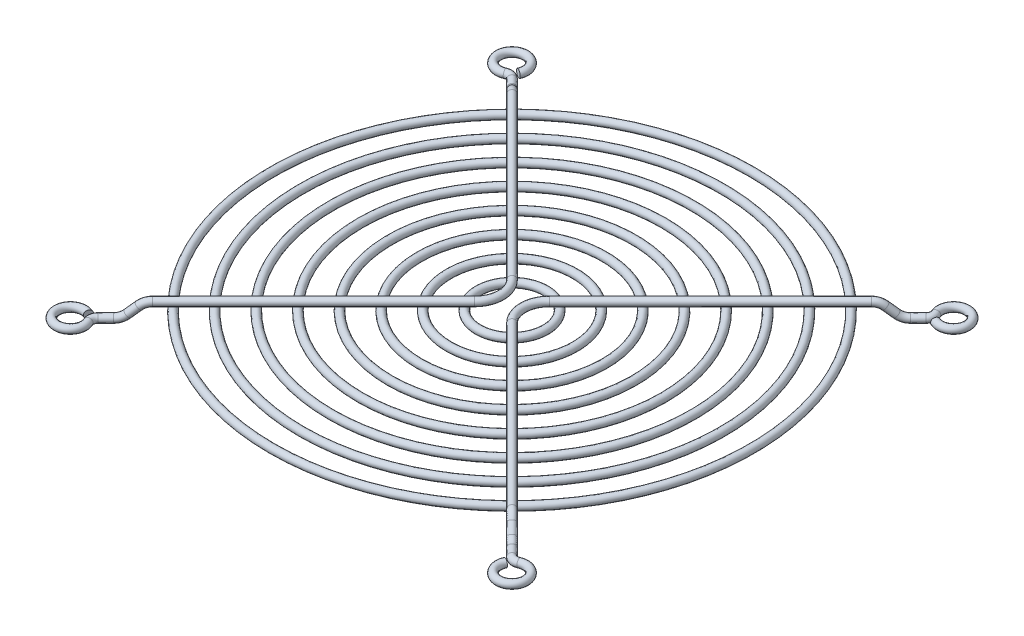
SolidWorks part; units mm, degrees
material "AISI 304"
ref_plane "Front" through (0, 0, 0) normal (0, 0, 1) x (1, 0, 0)
ref_plane "Top" through (0, 0, 0) normal (0, 1, 0) x (1, 0, 0)
ref_plane "Right" through (0, 0, 0) normal (1, 0, 0) x (0, 0, -1)
sketch "Sketch1" plane through (0, 0, 0) normal (0, 0, 1) x (1, 0, 0)
  line L0 (63.58, 0) -> (-63.58, 0) construction
  line L1 (-7.1, 2.8) -> (7.1, 2.8) construction
  line L2 (-57.8, 2.8) -> (57.8, 2.8) construction
  line L3 (0, 2.8) -> (0, 0) construction
  line L4 (-56.9, 2.8) -> (-49.9143, 2.8) construction
  line L5 (-49.9143, 2.8) -> (-42.9286, 2.8) construction
  line L6 (-42.9286, 2.8) -> (-35.9429, 2.8) construction
  line L7 (-35.9429, 2.8) -> (-28.9571, 2.8) construction
  line L8 (-28.9571, 2.8) -> (-21.9714, 2.8) construction
  line L9 (-21.9714, 2.8) -> (-14.9857, 2.8) construction
  line L10 (-14.9857, 2.8) -> (-8, 2.8) construction
  circle A0 centre (-8, 4.6) radius 0.9 construction
  circle A1 centre (-8, 2.8) radius 0.9
  circle A2 centre (-56.9, 2.8) radius 0.9
  circle A3 centre (-49.9143, 2.8) radius 0.9
  circle A4 centre (-42.9286, 2.8) radius 0.9
  circle A5 centre (-35.9429, 2.8) radius 0.9
  circle A6 centre (-28.9571, 2.8) radius 0.9
  circle A7 centre (-21.9714, 2.8) radius 0.9
  circle A8 centre (-14.9857, 2.8) radius 0.9
  point P4 (-8, 5.5)
  dimension "D2" = 1.8
  dimension "D5" = 1.8
  dimension "D1" = 5.5
  dimension "D3" = 14.2
  dimension "D4" = 115.6
revolve "Revolve1" add sketch "Sketch1" angle 360 mid plane about L3
sketch "Sketch2" plane through (0, 0, 0) normal (0, 1, 0) x (1, 0, 0)
  line L0 (-42.6385, 42.6385) -> (-4.4385, 4.4385)
  line L1 (0, -2.86) -> (0, 2.86) construction
  line L2 (-2.86, 0) -> (2.86, 0) construction
  line L3 (0, 0) -> (-52.4, -52.4) construction
  arc A0 (-4.4385, 4.4385) -> (-2.6, 0) centre (-8.877, 0) cw
  circle A1 centre (-2.6, 0) radius 0.9 construction
  circle A2 centre (0, 0) radius 57.8 construction
  circle A3 centre (-52.4, 52.4) radius 2.3 construction
  circle A4 centre (0, 0) radius 74.1048 construction
  circle A5 centre (-52.4, -52.4) radius 2.3 construction
  circle A6 centre (-52.4, 52.4) radius 4.1 construction
  point P9 (-3.5, 0)
  point P10 (-40.8708, 40.8708)
  dimension "D3" = 1.8
  dimension "D6" = 4.6
  dimension "D1" = 45
  dimension "D2" = 3.5
  dimension "D4" = 2.5
  dimension "D5" = 104.8
  dimension "D7" = 1.8
sketch "Sketch3" plane through (0, 0, 0) normal (0, 0, 1) x (1, 0, 0)
  circle A0 centre (-2.6, 4.6) radius 0.9
  circle A1 centre (-8, 4.6) radius 0.9 construction
sweep "Sweep1" add profiles "Sketch3" path "Sketch2"
ref_plane "Plane1" through (0, 0, 0) normal (0.7071, 0, -0.7071) x (-0.7071, 0, -0.7071)
sketch "Sketch4" plane through (0, 0, 0) normal (0.7071, 0, -0.7071) x (-0.7071, 0, -0.7071)
  line L0 (62.6607, 3.7179) -> (64.5441, 2.0821)
  line L3 (60.3, 3.7) -> (60.3, 5.5) construction
  line L5 (66.9048, 1.2) -> (70.9048, 1.2) construction
  line L10 (70.0048, 0) -> (71.8048, 0) construction
  arc A0 (60.3, 4.6) -> (62.6607, 3.7179) centre (60.3, 1) cw
  arc A1 (64.5441, 2.0821) -> (66.9048, 1.2) centre (66.9048, 4.8) ccw
  circle A2 centre (70.9048, 1.2) radius 1.2 construction
  point P9 (70.9048, 0)
  dimension "D1" = 3.6
  dimension "D3" = 2.4
  dimension "D2" = 4
sketch "Sketch5" plane through (-42.6385, 0, -42.6385) normal (-0.7071, 0, -0.7071) x (-0.7071, 0, 0.7071)
  circle A1 centre (0, 4.6) radius 0.9
  circle A2 centre (0, 4.6) radius 0.9
  dimension "D1" = 0
sweep "Sweep2" add profiles "Sketch5" path "Sketch4"
sketch "Sketch6" plane through (0, 0, 0) normal (0, 1, 0) x (1, 0, 0)
  line L1 (-49.1015, 49.1015) -> (-47.3088, 47.3088)
  line L2 (-49.507, 51.0323) -> (-52.4, 52.4) construction
  line L3 (-46.6724, 47.9452) -> (-47.9452, 46.6724) construction
  arc A0 (-51.1036, 49.4744) -> (-49.1015, 49.1015) centre (-50.3743, 47.8287) cw
  arc A2 (-49.507, 51.0323) -> (-51.1036, 49.4744) centre (-52.4, 52.4) ccw
  dimension "D1" = 1.8
  dimension "D2" = 1.9307
sketch "Sketch7" plane through (-47.3088, 0, -47.3088) normal (-0.7071, 0, -0.7071) x (-0.7071, 0, 0.7071)
  circle A1 centre (0, 1.2) radius 0.9
  circle A2 centre (0, 1.2) radius 0.9
  dimension "D1" = 0
sweep "Sweep3" add profiles "Sketch7" path "Sketch6"
sketch "Sketch8" plane through (0, 0, 0) normal (0, 1, 0) x (1, 0, 0)
  line L0 (-5.0749, 3.8021) -> (-3.8021, 5.0749)
  line L1 (-3.8021, 5.0749) -> (-5.0749, 3.8021) construction
  line L2 (-3.8021, 5.0749) -> (-42.0021, 43.2749) construction
extrude "Cut-Extrude1" cut sketch "Sketch8" against normal through all and the other way through all flip side to cut
pattern_circular "CirPattern1" count 4 over 360 about axis through (0, 0, 0) along (0, 1, 0) of bodies 114
sketch "Sketch9" plane through (0, 0, 0) normal (0, 1, 0) x (1, 0, 0)
  line L0 (-5.0749, 3.8021) -> (-3.8021, 5.0749) construction
  line L1 (-3.8021, -5.0749) -> (-5.0749, -3.8021) construction
  arc A0 (-4.4385, 4.4385) -> (-4.4385, -4.4385) centre (-8.877, 0) cw
sketch "Sketch10" plane through (-4.4385, 0, -4.4385) normal (0.7071, 0, 0.7071) x (0.7071, 0, -0.7071)
  circle A1 centre (0, 4.6) radius 0.9
  circle A2 centre (0, 4.6) radius 0.9
  dimension "D1" = 0
sweep "Sweep4" add profiles "Sketch10" path "Sketch9"
sketch "Sketch11" plane through (0, 0, 0) normal (0, 1, 0) x (1, 0, 0)
  line L0 (3.8021, 5.0749) -> (5.0749, 3.8021) construction
  line L1 (5.0749, -3.8021) -> (3.8021, -5.0749) construction
  arc A0 (4.4385, 4.4385) -> (4.4385, -4.4385) centre (8.877, 0) ccw
sketch "Sketch12" plane through (4.4385, 0, -4.4385) normal (-0.7071, 0, 0.7071) x (0.7071, 0, 0.7071)
  circle A1 centre (0, 4.6) radius 0.9
  circle A2 centre (0, 4.6) radius 0.9
  dimension "D1" = 0
sweep "Sweep5" add profiles "Sketch12" path "Sketch11"
sketch "Sketch13" plane through (0, 0, 0) normal (0, 0, 1) x (1, 0, 0)
  point P0 (-56.8752, 0)
  dimension "D1" = 56.8752
sketch "Sketch14" plane through (0, 0, 0) normal (0, 1, 0) x (1, 0, 0)
  line L0 (-59.5, 59.5) -> (59.5, -59.5) construction
  line L1 (-59.5, 59.5) -> (59.5, 59.5)
  line L2 (-59.5, 59.5) -> (-59.5, -59.5)
  line L3 (-59.5, -59.5) -> (59.5, -59.5)
  line L4 (59.5, 59.5) -> (59.5, -59.5)
  circle A0 centre (0, 0) radius 57.8 construction
  circle A1 centre (0, 0) radius 56 construction
  point P4 (-57.8, 0)
  point P5 (-56, 0)
  dimension "D1" = 119
sketch "Sketch15" plane through (0, 0, 0) normal (0, 1, 0) x (1, 0, 0)
  line L0 (-52.4, 52.4) -> (52.4, -52.4) construction
  line L1 (52.4, 52.4) -> (-52.4, -52.4) construction
equation "\"D1@Sketch4\" = \"D5@Sketch1\" * 2"
equation "\"D3@Sketch2\" = \"D5@Sketch1\""
equation "\"D7@Sketch2\" = \"D5@Sketch1\""
equation "\"D1@Sketch6\" = \"D5@Sketch1\""
